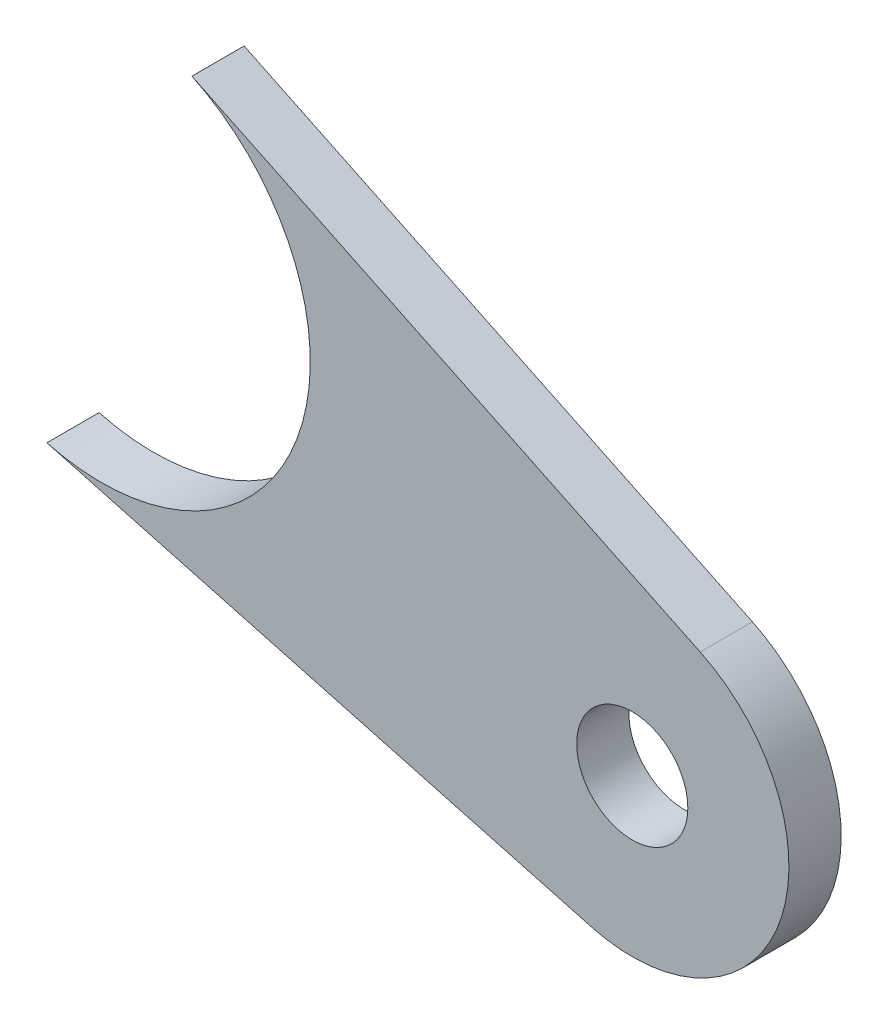
SolidWorks part; units mm, degrees
ref_plane "Front Plane" through (0, 0, 0) normal (0, 0, 1) x (1, 0, 0)
ref_plane "Top Plane" through (0, 0, 0) normal (0, 1, 0) x (1, 0, 0)
ref_plane "Right Plane" through (0, 0, 0) normal (1, 0, 0) x (0, 0, -1)
sketch "Sketch1" plane through (0, 0, 0) normal (0, 0, 1) x (1, 0, 0)
  line L0 (-101.5644, 0) -> (-133.8369, 12.0015) construction
  line L1 (-101.5644, 0) -> (-133.8369, 12.0015)
  line L2 (-128.3314, 23.4461) -> (-97.4353, 8.5835)
  line L3 (-137.1471, -0.2595) -> (-104.0471, -9.1958)
  circle A0 centre (-101.5644, 0) radius 3.3782 construction
  circle A1 centre (-101.5644, 0) radius 3.3782
  circle A2 centre (-101.5644, 0) radius 9.525
  circle A3 centre (-133.8369, 12.0015) radius 12.7
  dimension "D1" = 19.05
  dimension "D2" = 25.4
extrude "Boss-Extrude1" add sketch "Sketch1" along normal blind 3.175
